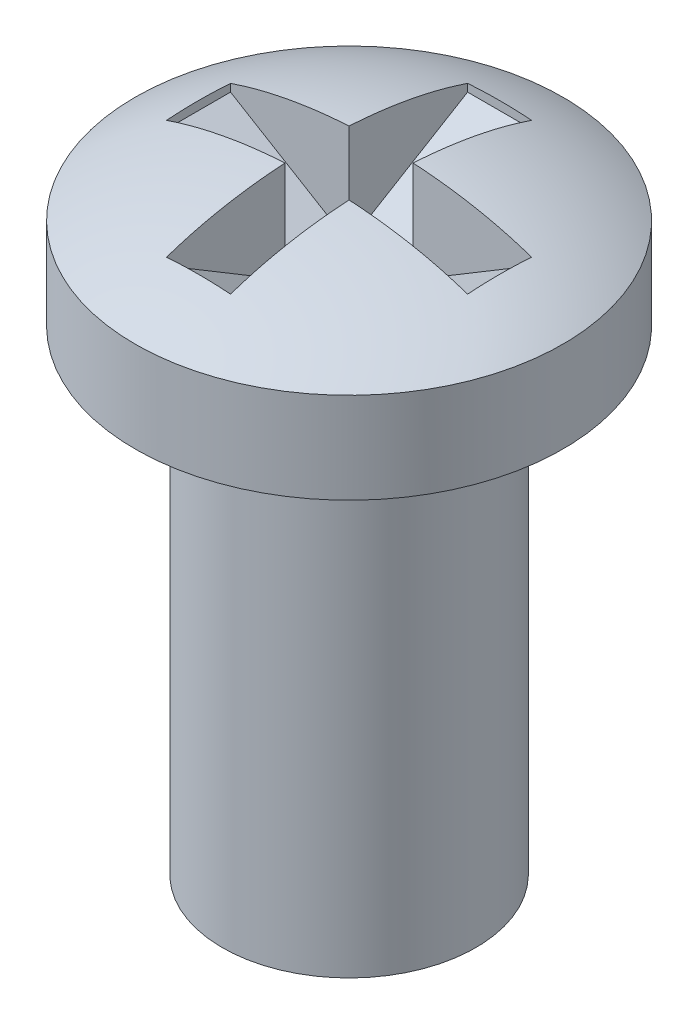
SolidWorks part; units mm, degrees
ref_plane "Front" through (0, 0, 0) normal (0, 0, 1) x (1, 0, 0)
ref_plane "Top" through (0, 0, 0) normal (0, 1, 0) x (1, 0, 0)
ref_plane "Right" through (0, 0, 0) normal (1, 0, 0) x (0, 0, -1)
sketch "草图2" plane through (0, 0, 0) normal (0, 0, 1) x (1, 0, 0)
  line L0 (0, 0) -> (0, -3.9) construction
  line L2 (1.35, -0.3265) -> (1.35, -0.9)
  line L3 (1.35, -0.9) -> (0.8, -0.9)
  line L4 (0.8, -0.9) -> (0.8, -3.9)
  line L5 (0.8, -3.9) -> (0, -3.9)
  line L6 (0, 0) -> (0, -3.9)
  spline S0 degree 3 poles (0, 0) (0.4632, 0) (0.9473, -0.0889) (1.35, -0.3265) knots 0 0 0 0 1 1 1 1
  point P8 (1.35, -0.2859)
  point P10 (0.7256, -0.1134)
  dimension "D1" = 1.35
  dimension "D3" = 0.8
  dimension "D4" = 3
revolve "旋转1" add sketch "草图2" angle 360 about L0
ref_plane "基准面2" through (0, 0, 0) normal (0, -1, 0) x (-1, 0, 0)
sketch "草图3" plane through (0, 0, 0) normal (0, -1, 0) x (-1, 0, 0)
  line L0 (-0.202, 0) -> (-0.202, 0.95)
  line L1 (-0.202, 0.95) -> (0.202, 0.95)
  line L3 (0.202, 0) -> (-0.202, 0)
  line L4 (0, 1.3421) -> (0, 0) construction
  line L5 (0.202, 0) -> (0.202, 0.95)
  dimension "D1" = 0.95
extrude "切除-拉伸1" cut sketch "草图3" along normal blind 0.2
pattern_circular "阵列(圆周)4" count 4 over 360 about axis through (0, 0, 0) along (0, 1, 0) of "切除-拉伸1"
sketch "草图6" plane through (0, 0, 0.202) normal (0, 0, -1) x (-1, 0, 0)
  line L0 (0.95, -0.2) -> (0, -0.7708)
  line L1 (0, -0.7708) -> (-0.95, -0.2)
  line L2 (-0.95, -0.2) -> (0.95, -0.2)
  line L3 (0, 0) -> (0, -0.7708) construction
  point P6 (0, 0.3708)
  point P8 (0, -0.9)
  point P9 (0, -0.7522)
  point P11 (0, 0)
  dimension "D1" = 118
extrude "切除-拉伸4" cut sketch "草图6" along normal up to surface (0.404 mm away) up to face at (-0.4825, -0.1234, -0.202)
sketch "草图7" plane through (0.202, 0, 0) normal (-1, 0, 0) x (0, 0, 1)
  line L7 (0.95, -0.2) -> (0, -0.7708)
  line L8 (-0.202, -0.7708) -> (0.202, -0.7708) construction
  line L9 (0, -0.7708) -> (-0.95, -0.2)
  line L10 (-0.95, -0.2) -> (-0.202, -0.2) construction
  line L11 (-0.95, -0.2) -> (0.95, -0.2)
extrude "切除-拉伸5" cut sketch "草图7" along normal up to surface (0.404 mm away) up to face at (-0.202, -0.131, -0.5551)
ref_plane "基准面1" through (0, -0.6494, 0) normal (0, -1, 0) x (-1, 0, 0)
sketch "草图8" plane through (0, -0.6494, 0) normal (0, -1, 0) x (-1, 0, 0)
  line L7 (-0.202, -0.202) -> (0.202, -0.202)
  line L8 (-0.202, -0.202) -> (-0.202, 0.202)
  line L9 (-0.202, 0.202) -> (0.202, 0.202)
  line L10 (0.202, -0.202) -> (0.202, 0.202)
  line L11 (-0.202, -0.202) -> (0.202, 0.202) construction
  line L12 (-0.202, 0.202) -> (0.202, -0.202) construction
  point P0 (0, 0)
extrude "凸台-拉伸1" add sketch "草图8" along normal blind 0.3
